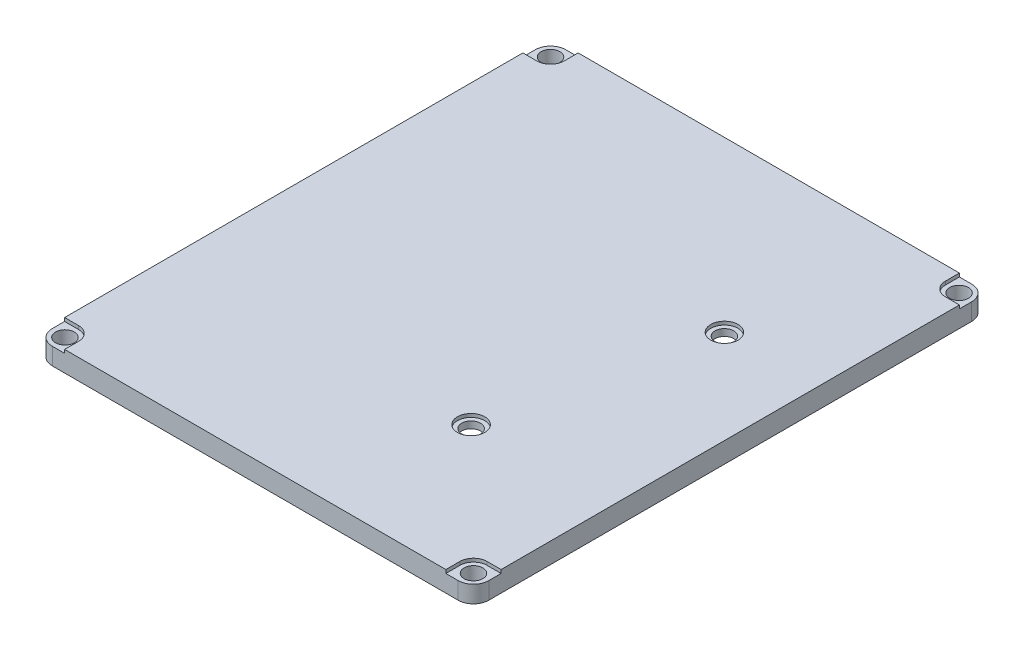
SolidWorks part; units mm, degrees
ref_plane "Front Plane" through (0, 0, 0) normal (0, 0, 1) x (1, 0, 0)
ref_plane "Top Plane" through (0, 0, 0) normal (0, 1, 0) x (1, 0, 0)
ref_plane "Right Plane" through (0, 0, 0) normal (1, 0, 0) x (0, 0, -1)
sketch "Sketch1" plane through (0, 26.4149, 0) normal (0, 1, 0) x (1, 0, 0)
  line L0 (-4.8921, -40.4499) -> (54.6079, -40.4499) construction
  line L1 (56.8579, -38.1999) -> (56.8579, 32.5943) construction
  line L2 (54.6079, 34.8443) -> (-4.8921, 34.8443) construction
  line L3 (-7.1421, 32.5943) -> (-7.1421, -38.1999) construction
  line L16 (-4.8921, -40.4499) -> (54.6079, -40.4499)
  line L17 (56.8579, -38.1999) -> (56.8579, 32.5943)
  line L18 (54.6079, 34.8443) -> (-4.8921, 34.8443)
  line L19 (-7.1421, 32.5943) -> (-7.1421, -38.1999)
  arc A0 (-7.1421, -38.1999) -> (-4.8921, -40.4499) centre (-4.8921, -38.1999) ccw construction
  arc A1 (54.6079, -40.4499) -> (56.8579, -38.1999) centre (54.6079, -38.1999) ccw construction
  arc A2 (56.8579, 32.5943) -> (54.6079, 34.8443) centre (54.6079, 32.5943) ccw construction
  arc A3 (-4.8921, 34.8443) -> (-7.1421, 32.5943) centre (-4.8921, 32.5943) ccw construction
  arc A16 (-7.1421, -38.1999) -> (-4.8921, -40.4499) centre (-4.8921, -38.1999) ccw
  arc A17 (54.6079, -40.4499) -> (56.8579, -38.1999) centre (54.6079, -38.1999) ccw
  arc A18 (56.8579, 32.5943) -> (54.6079, 34.8443) centre (54.6079, 32.5943) ccw
  arc A19 (-4.8921, 34.8443) -> (-7.1421, 32.5943) centre (-4.8921, 32.5943) ccw
extrude "Base" add sketch "Sketch1" along normal blind 3
sketch "Sketch2" plane through (0, 26.4149, 0) normal (0, -1, 0) x (1, 0, 0)
  line L0 (-3.6421, -31.3443) -> (-3.6421, -1.8443) construction
  line L1 (53.3579, -31.3443) -> (-3.6421, -31.3443) construction
  line L2 (53.3579, 36.9499) -> (53.3579, -31.3443) construction
  line L3 (-3.6421, 36.9499) -> (53.3579, 36.9499) construction
  line L4 (-3.6421, 36.9499) -> (53.3579, 36.9499) construction
  line L5 (-3.6421, 16.2499) -> (-3.6421, 36.9499) construction
  line L6 (-3.6421, -31.3443) -> (-3.6421, -1.8443) construction
  line L7 (53.3579, -31.3443) -> (-3.6421, -31.3443) construction
  line L8 (53.3579, 36.9499) -> (53.3579, -31.3443) construction
  line L9 (-3.6421, 36.9499) -> (53.3579, 36.9499) construction
  line L10 (-3.6421, 36.9499) -> (53.3579, 36.9499) construction
  line L11 (-3.6421, 16.2499) -> (-3.6421, 36.9499) construction
  line L13 (-3.6421, 36.9499) -> (53.3579, 36.9499)
  line L14 (-3.6421, 36.9499) -> (-3.6421, -31.3443)
  line L15 (-3.6421, -31.3443) -> (53.3579, -31.3443)
  line L16 (53.3579, 36.9499) -> (53.3579, -31.3443)
extrude "Shell" cut sketch "Sketch2" against normal blind 1.5
sketch "Sketch3" plane through (0, 29.4149, 0) normal (0, 1, 0) x (1, 0, 0)
  circle A18 centre (-5.0918, 32.7941) radius 1.125 construction
  circle A19 centre (-5.0918, -38.3996) radius 1.125 construction
  circle A20 centre (54.8077, -38.3996) radius 1.125 construction
  circle A21 centre (36.2579, -20.1996) radius 1.125 construction
  circle A22 centre (43.1079, 10.0943) radius 1.125 construction
  circle A23 centre (54.8077, 32.7941) radius 1.125 construction
  circle A24 centre (-5.0918, 32.7941) radius 1.125 construction
  circle A25 centre (-5.0918, -38.3996) radius 1.125 construction
  circle A26 centre (54.8077, -38.3996) radius 1.125 construction
  circle A27 centre (36.2579, -20.1996) radius 1.125 construction
  circle A28 centre (43.1079, 10.0943) radius 1.125 construction
  circle A29 centre (54.8077, 32.7941) radius 1.125 construction
  circle A30 centre (-5.0918, 32.7941) radius 1.375
  circle A31 centre (54.8077, 32.7941) radius 1.375
  circle A32 centre (43.1079, 10.0943) radius 1.375
  circle A33 centre (36.2579, -20.1996) radius 1.375
  circle A34 centre (54.8077, -38.3996) radius 1.375
  circle A35 centre (-5.0918, -38.3996) radius 1.375
  dimension "D1" = 2.75
  dimension "D2" = 2.75
  dimension "D3" = 2.75
  dimension "D4" = 2.75
  dimension "D5" = 2.75
  dimension "D6" = 2.75
extrude "Through Holes" cut sketch "Sketch3" against normal through all
sketch "Sketch6" plane through (0, 29.4149, 0) normal (0, 1, 0) x (1, 0, 0)
  line L4 (-4.8921, -40.4499) -> (54.6079, -40.4499)
  line L5 (-4.8921, -40.4499) -> (54.6079, -40.4499) construction
  line L6 (56.8579, -38.1999) -> (56.8579, 32.5943)
  line L7 (56.8579, -38.1999) -> (56.8579, 32.5943) construction
  line L25 (54.6079, 34.8443) -> (-4.8921, 34.8443) construction
  line L27 (54.6079, 34.8443) -> (-4.8921, 34.8443)
  line L29 (-7.1421, 32.5943) -> (-7.1421, -38.1999)
  line L30 (-7.1421, 32.5943) -> (-7.1421, -38.1999)
  line L31 (56.8579, -2.8028) -> (-7.1421, -2.8028) construction
  line L32 (24.8579, 34.8443) -> (24.8579, -40.4499) construction
  line L37 (54.8077, 30.7941) -> (56.8579, 30.7941)
  line L38 (52.8077, 32.7941) -> (52.8077, 34.8443)
  line L39 (52.8077, 34.8443) -> (56.8579, 34.8443)
  line L40 (56.8579, 34.8443) -> (56.8579, 30.7941)
  line L41 (-7.1421, 34.8443) -> (-7.1421, 30.7941)
  line L42 (-3.0918, 34.8443) -> (-7.1421, 34.8443)
  line L43 (-3.0918, 32.7941) -> (-3.0918, 34.8443)
  line L44 (-5.0918, 30.7941) -> (-7.1421, 30.7941)
  line L45 (-5.0918, -36.3996) -> (-7.1421, -36.3996)
  line L46 (-3.0918, -38.3996) -> (-3.0918, -40.4499)
  line L47 (-3.0918, -40.4499) -> (-7.1421, -40.4499)
  line L48 (-7.1421, -40.4499) -> (-7.1421, -36.3996)
  line L49 (56.8579, -40.4499) -> (56.8579, -36.3996)
  line L50 (52.8077, -40.4499) -> (56.8579, -40.4499)
  line L51 (52.8077, -38.3996) -> (52.8077, -40.4499)
  line L52 (54.8077, -36.3996) -> (56.8579, -36.3996)
  circle A0 centre (43.1079, 10.0943) radius 1.375 construction
  circle A3 centre (36.2579, -20.1996) radius 1.375 construction
  circle A6 centre (43.1079, 10.0943) radius 1.375 construction
  circle A9 centre (36.2579, -20.1996) radius 1.375 construction
  circle A13 centre (43.1079, 10.0943) radius 2
  circle A15 centre (36.2579, -20.1996) radius 2
  arc A21 (52.8077, 32.7941) -> (54.8077, 30.7941) centre (54.8077, 32.7941) ccw
  arc A22 (-7.1421, -38.1999) -> (-4.8921, -40.4499) centre (-4.8921, -38.1999) ccw
  arc A23 (54.6079, -40.4499) -> (56.8579, -38.1999) centre (54.6079, -38.1999) ccw
  arc A25 (56.8579, 32.5943) -> (54.6079, 34.8443) centre (54.6079, 32.5943) ccw
  arc A31 (-3.0918, 32.7941) -> (-5.0918, 30.7941) centre (-5.0918, 32.7941) cw
  arc A33 (-4.8921, 34.8443) -> (-7.1421, 32.5943) centre (-4.8921, 32.5943) ccw
  arc A34 (-3.0918, -38.3996) -> (-5.0918, -36.3996) centre (-5.0918, -38.3996) ccw
  arc A35 (52.8077, -38.3996) -> (54.8077, -36.3996) centre (54.8077, -38.3996) cw
  circle M1 centre (54.8077, 32.7941) radius 1.375
  circle M2 centre (43.1079, 10.0943) radius 1.375
  circle M3 centre (36.2579, -20.1996) radius 1.375
  circle M4 centre (54.8077, -38.3996) radius 1.375
  circle M5 centre (-5.0918, -38.3996) radius 1.375
  circle M6 centre (-5.0918, 32.7941) radius 1.375
  arc M7 (-7.1421, -38.1999) -> (-4.8921, -40.4499) centre (-4.8921, -38.1999) ccw
  line M62 (-4.8921, -40.4499) -> (54.6079, -40.4499)
  arc M63 (54.6079, -40.4499) -> (56.8579, -38.1999) centre (54.6079, -38.1999) ccw
  line M64 (56.8579, -38.1999) -> (56.8579, 32.5943)
  arc M65 (56.8579, 32.5943) -> (54.6079, 34.8443) centre (54.6079, 32.5943) ccw
  line M66 (54.6079, 34.8443) -> (-4.8921, 34.8443)
  arc M67 (-4.8921, 34.8443) -> (-7.1421, 32.5943) centre (-4.8921, 32.5943) ccw
  line M68 (-7.1421, 32.5943) -> (-7.1421, -38.1999)
  dimension "D1" = 4
  dimension "D5" = 4
  dimension "D2" = 4
  dimension "D7" = 0
extrude "Socket Holes" cut sketch "Sketch6" against normal blind 0.5 contours L46 A34 L45 M68 M7 M62 M5 | A15 M3 | A35 L51 L52 M62 M63 M64 M4 | A13 M2 | L38 A21 L37 M64 M65 M66 M1 | A31 L43 L44 M66 M67 M68 M6
sketch "Sketch7" plane through (0, 27.9149, 0) normal (0, -1, 0) x (1, 0, 0)
  line L1 (4.5076, 34.5251) -> (13.0076, 34.5251)
  line L2 (4.5076, 34.5251) -> (4.5076, 26.0251)
  line L3 (4.5076, 26.0251) -> (13.0076, 26.0251)
  line L4 (13.0076, 34.5251) -> (13.0076, 26.0251)
  line L8 (13.5076, 35.0251) -> (4.0076, 35.0251)
  line L9 (13.5076, 25.0251) -> (13.5076, 35.0251)
  line L10 (12.5076, 25.0251) -> (13.5076, 25.0251)
  line L11 (12.5076, 25.5251) -> (12.5076, 25.0251)
  line L12 (5.0076, 25.5251) -> (12.5076, 25.5251)
  line L13 (5.0076, 25.0251) -> (5.0076, 25.5251)
  line L14 (4.0076, 25.0251) -> (5.0076, 25.0251)
  line L15 (4.0076, 35.0251) -> (4.0076, 25.0251)
  line L16 (13.5076, 35.0251) -> (4.0076, 35.0251) construction
  line L17 (13.5076, 25.0251) -> (13.5076, 35.0251) construction
  line L18 (12.5076, 25.0251) -> (13.5076, 25.0251) construction
  line L19 (12.5076, 25.5251) -> (12.5076, 25.0251) construction
  line L20 (5.0076, 25.5251) -> (12.5076, 25.5251) construction
  line L21 (5.0076, 25.0251) -> (5.0076, 25.5251) construction
  line L22 (4.0076, 25.0251) -> (5.0076, 25.0251) construction
  line L23 (4.0076, 35.0251) -> (4.0076, 25.0251) construction
  dimension "D2" = 0.5
  dimension "D3" = 0.5
  dimension "D4" = 0.5
  dimension "D5" = 0.5
extrude "Boss-Extrude2" add sketch "Sketch7" along normal offset from surface (2.8 mm away) 0.25
sketch "Sketch8" plane through (0, 27.9149, 0) normal (0, -1, 0) x (1, 0, 0)
  line L0 (24.8433, 23.4508) -> (26.2743, 23.4508) construction
  line L1 (26.2743, 23.4508) -> (26.2743, 20.799) construction
  line L2 (25.2743, 19.799) -> (17.3885, 19.799) construction
  line L3 (17.3885, 19.799) -> (15.9743, 21.2132) construction
  line L4 (15.9743, 21.2132) -> (15.9743, 23.4508) construction
  line L5 (15.9743, 23.4508) -> (17.3121, 23.4508) construction
  line L6 (26.2743, 26.3508) -> (24.7046, 26.3508) construction
  line L7 (17.4508, 26.3508) -> (15.9743, 26.3508) construction
  line L8 (15.9743, 26.3508) -> (15.9743, 28.5884) construction
  line L9 (15.9743, 28.5884) -> (17.035, 29.649) construction
  line L10 (17.035, 29.649) -> (24.8601, 29.649) construction
  line L11 (24.8601, 29.649) -> (26.2743, 28.2348) construction
  line L12 (26.2743, 28.2348) -> (26.2743, 26.3508) construction
  line L13 (24.8433, 23.4508) -> (26.2743, 23.4508) construction
  line L14 (26.2743, 23.4508) -> (26.2743, 20.799)
  line L15 (25.2743, 19.799) -> (17.3885, 19.799)
  line L16 (17.3885, 19.799) -> (15.9743, 21.2132)
  line L17 (15.9743, 21.2132) -> (15.9743, 23.4508)
  line L18 (15.9743, 23.4508) -> (17.3121, 23.4508) construction
  line L19 (26.2743, 26.3508) -> (24.7046, 26.3508) construction
  line L20 (17.4508, 26.3508) -> (15.9743, 26.3508) construction
  line L21 (15.9743, 26.3508) -> (15.9743, 28.5884)
  line L22 (15.9743, 28.5884) -> (17.035, 29.649)
  line L23 (17.035, 29.649) -> (24.8601, 29.649)
  line L24 (24.8601, 29.649) -> (26.2743, 28.2348)
  line L25 (26.2743, 28.2348) -> (26.2743, 26.3508)
  line L26 (15.9743, 26.3508) -> (15.9743, 23.4508)
  line L27 (26.2743, 26.3508) -> (26.2743, 23.4508)
  arc A0 (17.3121, 23.4508) -> (24.8433, 23.4508) centre (21.0777, 24.724) ccw construction
  arc A1 (25.2743, 19.799) -> (26.2743, 20.799) centre (25.2743, 20.799) ccw construction
  arc A2 (24.7046, 26.3508) -> (21.0777, 28.699) centre (21.0777, 24.724) ccw construction
  arc A3 (21.0777, 28.699) -> (17.4508, 26.3508) centre (21.0777, 24.724) ccw construction
  arc A4 (17.3121, 23.4508) -> (24.8433, 23.4508) centre (21.0777, 24.724) ccw construction
  arc A5 (25.2743, 19.799) -> (26.2743, 20.799) centre (25.2743, 20.799) ccw
  arc A6 (24.7046, 26.3508) -> (21.0777, 28.699) centre (21.0777, 24.724) ccw construction
  arc A7 (21.0777, 28.699) -> (17.4508, 26.3508) centre (21.0777, 24.724) ccw construction
extrude "Boss-Extrude3" add sketch "Sketch8" along normal offset from surface (4.1 mm away) 0.25
sketch "Sketch9" plane through (0, 27.9149, 0) normal (0, -1, 0) x (1, 0, 0)
  line L4 (4.0282, 5.2947) -> (8.9282, 5.2947)
  line L5 (4.0282, 8.6184) -> (4.0282, 5.2947)
  line L6 (8.9282, 8.6184) -> (4.0282, 8.6184)
  line L7 (8.9282, 5.2947) -> (8.9282, 8.6184)
  line L8 (4.0282, 5.2947) -> (8.9282, 5.2947)
  line L9 (4.0282, 8.6184) -> (4.0282, 5.2947)
  line L10 (8.9282, 8.6184) -> (4.0282, 8.6184)
  line L11 (8.9282, 5.2947) -> (8.9282, 8.6184)
  dimension "D1" = 0
extrude "Boss-Extrude4" add sketch "Sketch9" along normal offset from surface (6.0282 mm away) 0.25
sketch "Sketch10" plane through (0, 27.9149, 0) normal (0, -1, 0) x (1, 0, 0)
  line L4 (19.1435, 11.7589) -> (16.3382, 11.7589)
  line L5 (19.1435, 7.6537) -> (19.1435, 11.7589)
  line L6 (16.3382, 7.6537) -> (19.1435, 7.6537)
  line L7 (16.3382, 11.7589) -> (16.3382, 7.6537)
  line L8 (19.1435, 11.7589) -> (16.3382, 11.7589)
  line L9 (19.1435, 7.6537) -> (19.1435, 11.7589)
  line L10 (16.3382, 7.6537) -> (19.1435, 7.6537)
  line L11 (16.3382, 11.7589) -> (16.3382, 7.6537)
  dimension "D1" = 0
extrude "Boss-Extrude5" add sketch "Sketch10" along normal offset from surface (6.5752 mm away) 0.25
equation "\"cover height\"= 3"
equation "\"D1@Base\" = \"cover height\""
equation "\"cover thickness\"= 1.5"
equation "\"D1@Shell\" = \"cover height\" - \"cover thickness\""
equation "\"tolerance\"= 0.5"
equation "\"through hole\"= 2.75"
equation "\"screw head size\"= 4"
equation "\"screw head depth\"= 0.5"
equation "\"D1@Sketch6\"=\"screw head size\""
equation "\"D5@Sketch6\"=\"screw head size\""
equation "\"D1@Socket Holes\" = \"screw head depth\""
equation "\"D2@Sketch7\"=\"tolerance\""
equation "\"D3@Sketch7\"=\"tolerance\""
equation "\"D4@Sketch7\"=\"tolerance\""
equation "\"D5@Sketch7\"=\"tolerance\""
equation "\"height tolerance\"=0.25"
equation "\"D1@Boss-Extrude2\"=\"height tolerance\""
equation "\"D1@Sketch3\"=\"through hole\""
equation "\"D2@Sketch3\"=\"through hole\""
equation "\"D3@Sketch3\"=\"through hole\""
equation "\"D4@Sketch3\"=\"through hole\""
equation "\"D5@Sketch3\"=\"through hole\""
equation "\"D6@Sketch3\"=\"through hole\""
equation "\"fillet radius\"= 1"
equation "\"D1@Boss-Extrude3\"=\"height tolerance\""
equation "\"D1@Boss-Extrude4\"=\"height tolerance\""
equation "\"D1@Boss-Extrude5\"=\"height tolerance\""
equation "\"D2@Sketch6\"=\"screw head size\""
